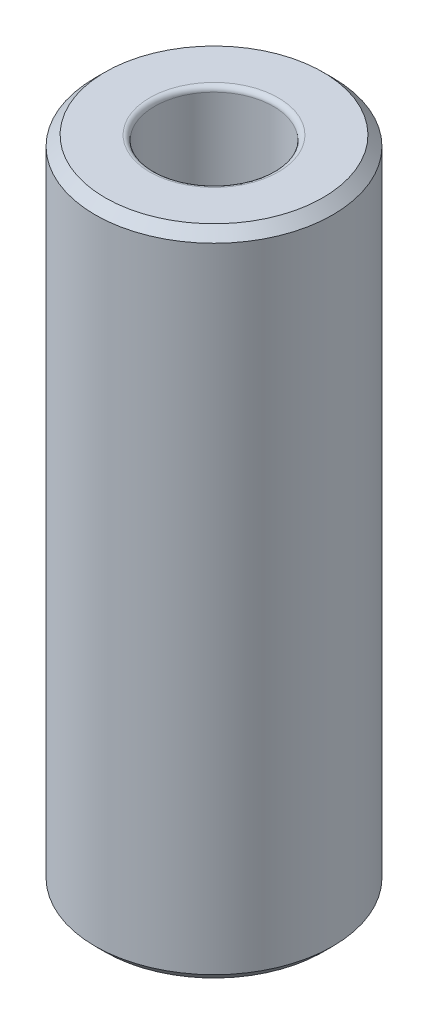
SolidWorks part; units mm, degrees
material "Stainless Steel (ferritic)"
ref_plane "Front Plane" through (0, 0, 0) normal (0, 0, 1) x (1, 0, 0)
ref_plane "Top Plane" through (0, 0, 0) normal (0, 1, 0) x (1, 0, 0)
ref_plane "Right Plane" through (0, 0, 0) normal (1, 0, 0) x (0, 0, -1)
sketch "Sketch1" plane through (0, 0, 0) normal (0, 1, 0) x (1, 0, 0)
  circle A0 centre (0, 0) radius 3
  circle A1 centre (0, 0) radius 1.5
  dimension "D1" = 3
  dimension "D2" = 6
extrude "Boss-Extrude1" add sketch "Sketch1" along normal blind 16.5 contours A0 A1
chamfer "Chamfer1" distance 0.25 angle 45 2 edges at (0, 0, 3) (0, 16.5, 3)
fillet "Fillet1" radius 0.125 2 edges at (0, 0, 1.5) (0, 16.5, 1.5)
